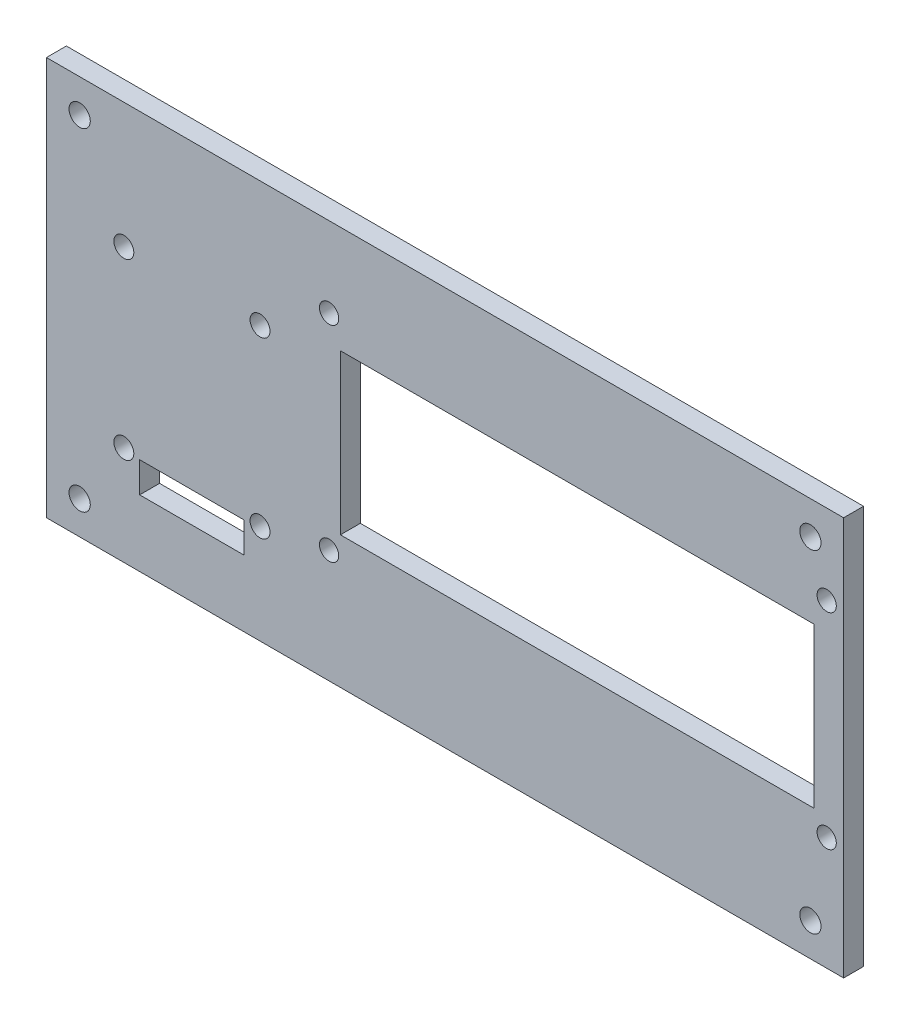
SolidWorks part; units mm, degrees
ref_plane "Front Plane" through (0, 0, 0) normal (0, 0, 1) x (1, 0, 0)
ref_plane "Top Plane" through (0, 0, 0) normal (0, 1, 0) x (1, 0, 0)
ref_plane "Right Plane" through (0, 0, 0) normal (1, 0, 0) x (0, 0, -1)
sketch "Sketch1" plane through (0, 0, 0) normal (0, 0, 1) x (1, 0, 0)
  line L1 (-56.9074, 24.37) -> (63.0926, 24.37)
  line L2 (-56.9074, 24.37) -> (-56.9074, -35.63)
  line L3 (-56.9074, -35.63) -> (63.0926, -35.63)
  line L4 (63.0926, 24.37) -> (63.0926, -35.63)
  dimension "D1" = 60
  dimension "D2" = 120
extrude "Boss-Extrude1" add sketch "Sketch1" along normal blind 3
sketch "Sketch2" plane through (0, 0, 0) normal (0, 0, -1) x (-1, 0, 0)
  circle A0 centre (-58.0926, 19.37) radius 1.5
  circle A1 centre (51.9074, 19.37) radius 1.5
  circle A2 centre (51.9074, -30.63) radius 1.5
  circle A3 centre (-58.0926, -30.63) radius 1.5
sketch "Sketch3" plane through (0, 0, 3) normal (0, 0, 1) x (1, 0, 0)
  circle A0 centre (58.0926, 19.37) radius 1.6
  circle A1 centre (58.0926, -30.63) radius 1.6
  circle A2 centre (-51.9074, -30.63) radius 1.6
  circle A3 centre (-51.9074, 19.37) radius 1.6
extrude "Cut-Extrude2" cut sketch "Sketch3" against normal through all
sketch "Sketch5" plane through (0, 0, 0) normal (0, 0, -1) x (-1, 0, 0)
  circle A0 centre (14.3574, 12.32) radius 1.45
  circle A1 centre (14.3574, -18.58) radius 1.45
  circle A2 centre (-60.5426, -18.58) radius 1.45
  circle A3 centre (-60.5426, 12.32) radius 1.45
extrude "Cut-Extrude4" cut sketch "Sketch5" against normal through all
sketch "Sketch7" plane through (0, 0, 3) normal (0, 0, 1) x (1, 0, 0)
  line L1 (-12.6574, 8.27) -> (58.6426, 8.27)
  line L2 (-12.6574, 8.27) -> (-12.6574, -15.73)
  line L3 (-12.6574, -15.73) -> (58.6426, -15.73)
  line L4 (58.6426, 8.27) -> (58.6426, -15.73)
extrude "Cut-Extrude5" cut sketch "Sketch7" against normal through all
sketch "Sketch8" plane through (0, 0, 3) normal (0, 0, 1) x (1, 0, 0)
  line L0 (-48.1074, -25.63) -> (-21.9074, -25.63) construction
  line L1 (-42.8747, -25.63) -> (-27.1849, -25.63)
  line L2 (-42.8747, -25.63) -> (-42.8747, -21.0438)
  line L3 (-42.8747, -21.0438) -> (-27.1849, -21.0438)
  line L4 (-27.1849, -25.63) -> (-27.1849, -21.0438)
  circle A0 centre (-45.2574, 5.52) radius 1.5
  circle A1 centre (-24.7574, 5.52) radius 1.5
  circle A2 centre (-24.7574, -20.68) radius 1.5
  circle A3 centre (-45.2574, -20.68) radius 1.5
extrude "Cut-Extrude6" cut sketch "Sketch8" against normal through all
